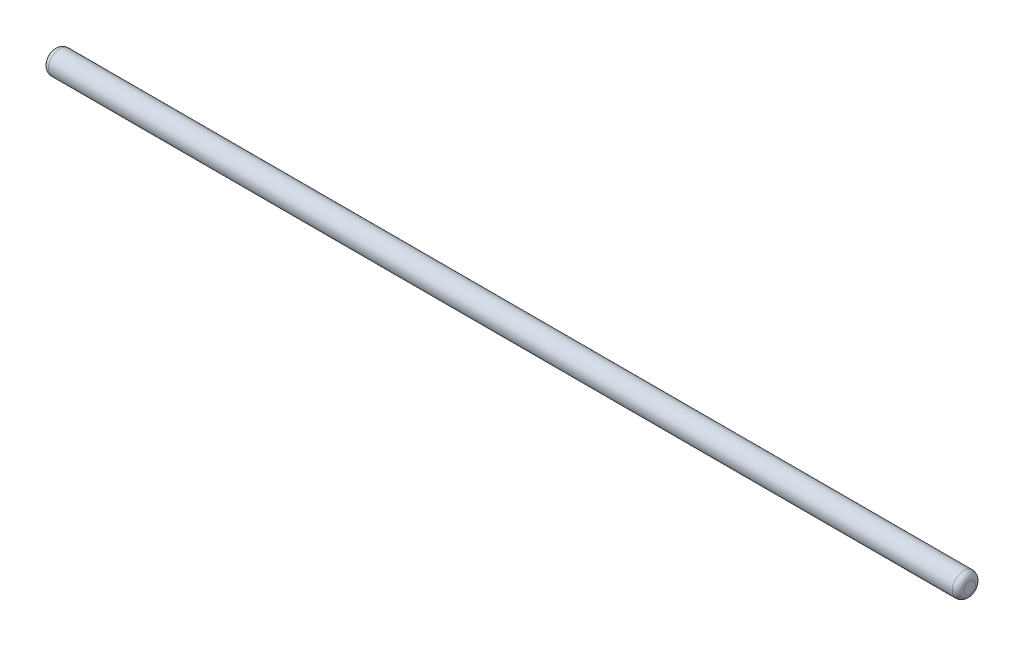
SolidWorks part; units mm, degrees
ref_plane "Front Plane" through (0, 0, 0) normal (0, 0, 1) x (1, 0, 0)
ref_plane "Top Plane" through (0, 0, 0) normal (0, 1, 0) x (1, 0, 0)
ref_plane "Right Plane" through (0, 0, 0) normal (1, 0, 0) x (0, 0, -1)
sketch "Sketch1" plane through (0, 0, 0) normal (1, 0, 0) x (0, 0, -1)
  circle A0 centre (0, 0) radius 2
extrude "Boss-Extrude1" add sketch "Sketch1" along normal blind 157
fillet "Fillet1" radius 1 2 edges at (0, 0, -2) (157, 0, -2)
